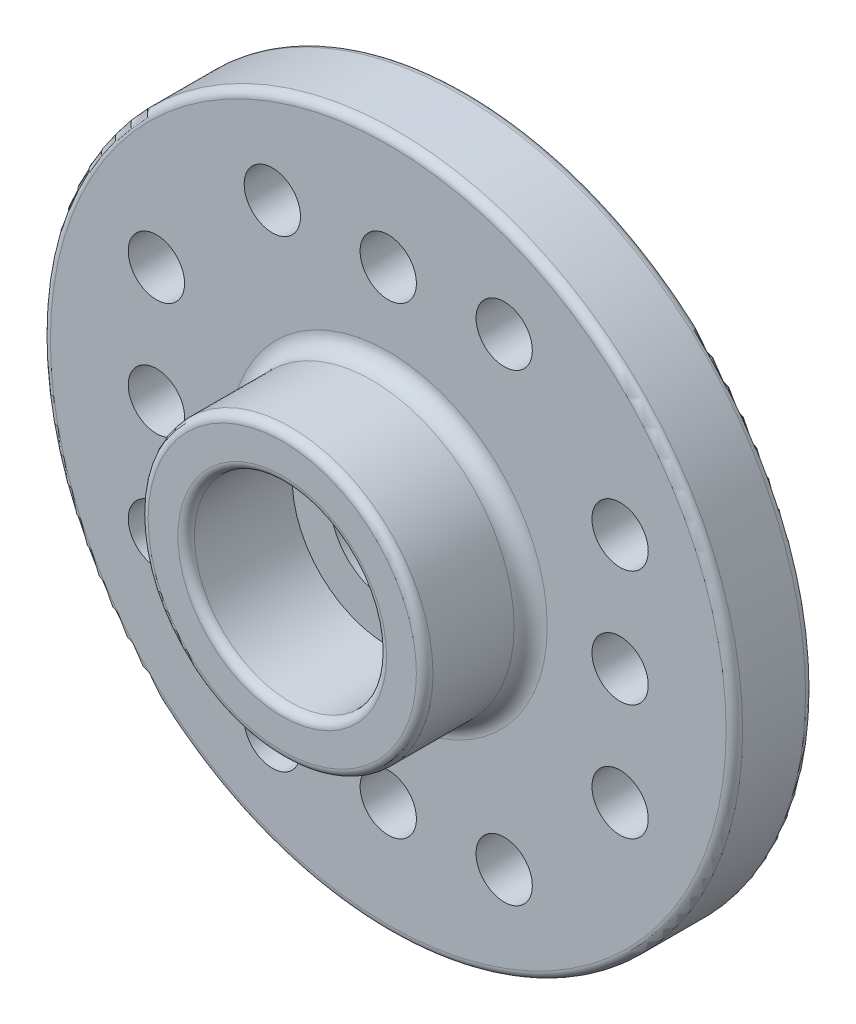
SolidWorks part; units mm, degrees
ref_plane "Front Plane" through (0, 0, 0) normal (0, 0, 1) x (1, 0, 0)
ref_plane "Top Plane" through (0, 0, 0) normal (0, 1, 0) x (1, 0, 0)
ref_plane "Right Plane" through (0, 0, 0) normal (1, 0, 0) x (0, 0, -1)
sketch "Sketch1" plane through (0, 0, 0) normal (0, 0, 1) x (1, 0, 0)
  circle A0 centre (0, 0) radius 10.45
  circle A1 centre (0, 0) radius 1.75
  dimension "D1" = 20.9
  dimension "D2" = 3.5
extrude "Boss-Extrude1" add sketch "Sketch1" along normal blind 2.4
sketch "Sketch2" plane through (0, 0, 2.4) normal (0, 0, 1) x (1, 0, 0)
  circle A0 centre (0, 0) radius 4.3
  circle A1 centre (0, 0) radius 2.9
  dimension "D1" = 8.6
  dimension "D2" = 5.8
extrude "Boss-Extrude2" add sketch "Sketch2" along normal blind 3.2
sketch "Sketch4" plane through (0, 0, 0) normal (0, 0, -1) x (-1, 0, 0)
  circle A0 centre (0, 0) radius 3.3
  circle A1 centre (0, 0) radius 3.6
  dimension "D1" = 7.2
  dimension "D2" = 6.6
extrude "Boss-Extrude3" add sketch "Sketch4" along normal blind 0.2
sketch "Sketch5" plane through (0, 0, 0) normal (0, 0, -1) x (-1, 0, 0)
  circle A0 centre (0, 0) radius 3.3 construction
  circle A1 centre (0, 0) radius 3.3
  circle A2 centre (0, 0) radius 4
  circle A3 centre (0, 0) radius 3.6 construction
  circle A4 centre (0, 0) radius 3.6
  circle M2 centre (0, 0) radius 3.6
  dimension "D1" = 8
extrude "Cut-Extrude2" cut sketch "Sketch5" against normal blind 0.4 contours A1 | A2 M2
sketch "Sketch6" plane through (0, 0, 0) normal (0, 0, -1) x (-1, 0, 0)
  line L0 (0, 0) -> (0, 7) construction
  circle A0 centre (0, 7) radius 0.85
  circle A1 centre (3.5, 7) radius 0.85
  circle A2 centre (-3.5, 7) radius 0.85
  dimension "D1" = 1.7
  dimension "D2" = 3.5
  dimension "D3" = 3.5
  dimension "D4" = 7
extrude "Cut-Extrude3" cut sketch "Sketch6" against normal through all
pattern_circular "CirPattern1" count 4 over 360 about axis through (0, 0, 0) along (0, 0, 1) of "Cut-Extrude3"
fillet "Fillet1" radius 0.25 4 edges at (4.3, 0, 5.6) (10.45, 0, 2.4) (10.45, 0, 0) (2.9, 0, 5.6)
fillet "Fillet2" radius 0.5 1 edges at (4.3, 0, 2.4)
